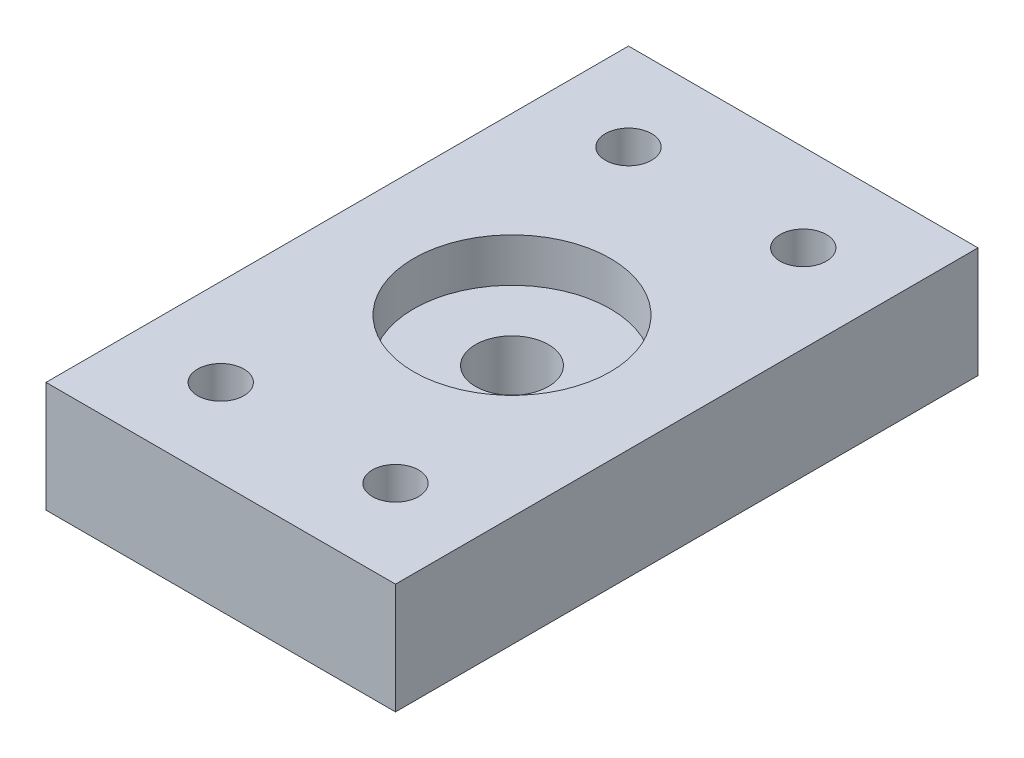
SolidWorks part; units mm, degrees
material "6061 Alloy"
ref_plane "Front Plane" through (0, 0, 0) normal (0, 0, 1) x (1, 0, 0)
ref_plane "Top Plane" through (0, 0, 0) normal (0, 1, 0) x (1, 0, 0)
ref_plane "Right Plane" through (0, 0, 0) normal (1, 0, 0) x (0, 0, -1)
sketch "Sketch1" plane through (0, 0, 0) normal (0, 1, 0) x (1, 0, 0)
  line L1 (-38.1, -63.5) -> (38.1, -63.5)
  line L2 (-38.1, -63.5) -> (-38.1, 63.5)
  line L3 (-38.1, 63.5) -> (38.1, 63.5)
  line L4 (38.1, -63.5) -> (38.1, 63.5)
  line L5 (-38.1, -63.5) -> (38.1, 63.5) construction
  line L6 (-38.1, 63.5) -> (38.1, -63.5) construction
  point P0 (0, 0)
  dimension "D1" = 76.2
  dimension "D2" = 127
extrude "Boss-Extrude1" add sketch "Sketch1" along normal blind 24.13
sketch "Sketch2" plane through (0, 24.13, 0) normal (0, 1, 0) x (1, 0, 0)
  circle A0 centre (0, 0) radius 7.9375
  dimension "D1" = 15.875
extrude "1/2\"-13 Threaded Hole" cut sketch "Sketch2" against normal through all
sketch "Sketch3" plane through (0, 24.13, 0) normal (0, 1, 0) x (1, 0, 0)
  circle A0 centre (-19.05, 44.45) radius 5.0419
  circle A1 centre (19.05, 44.45) radius 5.0419
  circle A2 centre (19.05, -44.45) radius 5.0419
  circle A3 centre (-19.05, -44.45) radius 5.0419
  dimension "D5" = 10.0838
  dimension "D1" = 44.45
  dimension "D2" = 44.45
  dimension "D3" = 19.05
  dimension "D4" = 19.05
extrude "3/8\" Through Holes" cut sketch "Sketch3" against normal through all
sketch "Sketch4" plane through (0, 24.13, 0) normal (0, 1, 0) x (1, 0, 0)
  circle A0 centre (0, 0) radius 21.4312
  dimension "D1" = 42.8625
extrude "Cut-Extrude1" cut sketch "Sketch4" against normal blind 9.525
